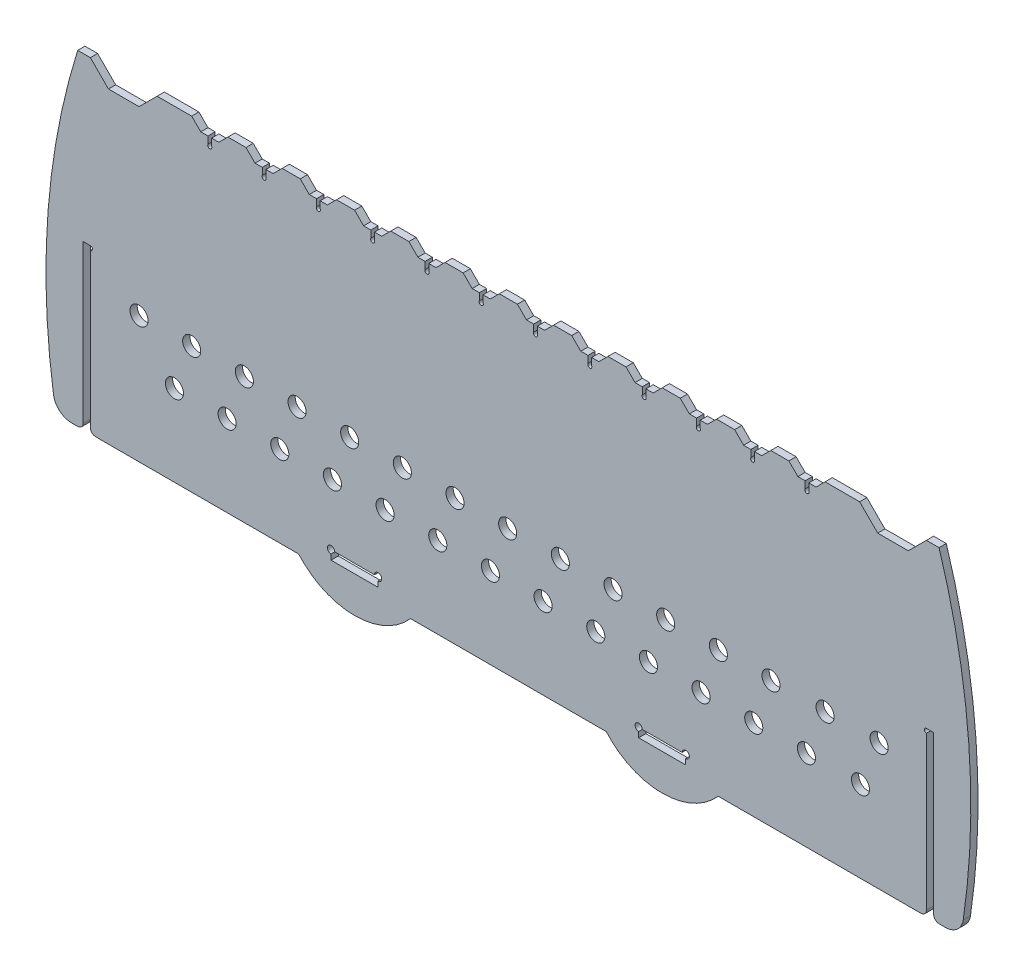
SolidWorks part; units mm, degrees
ref_plane "Спереди" through (0, 0, 0) normal (0, 0, 1) x (1, 0, 0)
ref_plane "Сверху" through (0, 0, 0) normal (0, 1, 0) x (1, 0, 0)
ref_plane "Справа" through (0, 0, 0) normal (1, 0, 0) x (0, 0, -1)
sketch "Эскиз1" plane through (0, 0, 0) normal (0, 0, 1) x (1, 0, 0)
  line L0 (152, 6) -> (178, 6)
  line L1 (8.5269, 0) -> (12, 0)
  line L2 (152, 6) -> (152, 9)
  line L3 (55.8972, 180) -> (45.8972, 170)
  line L4 (178, 6) -> (178, 9)
  line L5 (154, 11) -> (176, 11)
  line L6 (15, 3) -> (15, 90)
  line L7 (485, 3) -> (485, 90)
  line L8 (19, 87.6915) -> (19, 3)
  line L9 (481, 87.6915) -> (481, 3)
  line L10 (29, 170) -> (45.8972, 170)
  line L11 (84, 175) -> (84, 171.1094)
  line L12 (86, 175) -> (86, 171.1094)
  line L13 (84, 175) -> (80, 175)
  line L14 (322, 6) -> (348, 6)
  line L15 (22, 0) -> (134.0741, 0)
  line L16 (324, 11) -> (346, 11)
  line L17 (195.9259, 0) -> (304.0741, 0)
  line L18 (485, 90) -> (481, 90)
  line L19 (365.9259, 0) -> (478, 0)
  line L20 (444.1028, 180) -> (454.1028, 170)
  line L21 (488, 0) -> (491.4731, 0)
  line L22 (348, 6) -> (348, 9)
  line L23 (114, 175) -> (114, 171.1094)
  line L24 (116, 175) -> (116, 171.1094)
  line L25 (19, 180) -> (29, 170)
  line L26 (481, 180) -> (471, 170)
  line L27 (19, 180) -> (12, 180)
  line L28 (481, 180) -> (488, 180)
  line L29 (19, 90) -> (15, 90)
  line L30 (322, 6) -> (322, 9)
  line L31 (144, 175) -> (144, 171.1094)
  line L32 (146, 175) -> (146, 171.1094)
  line L33 (174, 175) -> (174, 171.1094)
  line L34 (176, 175) -> (176, 171.1094)
  line L35 (204, 175) -> (204, 171.1094)
  line L36 (206, 175) -> (206, 171.1094)
  line L37 (234, 175) -> (234, 171.1094)
  line L38 (236, 175) -> (236, 171.1094)
  line L39 (264, 175) -> (264, 171.1094)
  line L40 (266, 175) -> (266, 171.1094)
  line L41 (294, 175) -> (294, 171.1094)
  line L42 (296, 175) -> (296, 171.1094)
  line L43 (324, 175) -> (324, 171.1094)
  line L44 (326, 175) -> (326, 171.1094)
  line L45 (354, 175) -> (354, 171.1094)
  line L46 (356, 175) -> (356, 171.1094)
  line L47 (384, 175) -> (384, 171.1094)
  line L48 (386, 175) -> (386, 171.1094)
  line L49 (414, 175) -> (414, 171.1094)
  line L50 (416, 175) -> (416, 171.1094)
  line L51 (114, 175) -> (110, 175)
  line L52 (144, 175) -> (140, 175)
  line L53 (174, 175) -> (170, 175)
  line L54 (204, 175) -> (200, 175)
  line L55 (234, 175) -> (230, 175)
  line L56 (264, 175) -> (260, 175)
  line L57 (294, 175) -> (290, 175)
  line L58 (324, 175) -> (320, 175)
  line L59 (354, 175) -> (350, 175)
  line L60 (384, 175) -> (380, 175)
  line L61 (414, 175) -> (410, 175)
  line L119 (245, 180) -> (255, 180)
  line L120 (105, 180) -> (110, 175)
  line L122 (180, 175) -> (176, 175)
  line L127 (150, 175) -> (146, 175)
  line L128 (300, 175) -> (296, 175)
  line L129 (345, 180) -> (350, 175)
  line L130 (155, 180) -> (165, 180)
  line L131 (185, 180) -> (195, 180)
  line L133 (75, 180) -> (80, 175)
  line L134 (125, 180) -> (120, 175)
  line L137 (345, 180) -> (335, 180)
  line L140 (215, 180) -> (210, 175)
  line L142 (285, 180) -> (290, 175)
  line L146 (215, 180) -> (225, 180)
  line L147 (270, 175) -> (266, 175)
  line L150 (390, 175) -> (386, 175)
  line L151 (375, 180) -> (380, 175)
  line L153 (444.1028, 180) -> (425, 180)
  line L156 (155, 180) -> (150, 175)
  line L160 (405, 180) -> (395, 180)
  line L164 (365, 180) -> (360, 175)
  line L165 (285, 180) -> (275, 180)
  line L166 (90, 175) -> (86, 175)
  line L167 (255, 180) -> (260, 175)
  line L168 (120, 175) -> (116, 175)
  line L170 (471, 170) -> (454.1028, 170)
  line L171 (375, 180) -> (365, 180)
  line L172 (55.8972, 180) -> (75, 180)
  line L173 (165, 180) -> (170, 175)
  line L174 (210, 175) -> (206, 175)
  line L175 (305, 180) -> (300, 175)
  line L176 (330, 175) -> (326, 175)
  line L177 (360, 175) -> (356, 175)
  line L179 (125, 180) -> (135, 180)
  line L182 (405, 180) -> (410, 175)
  line L183 (420, 175) -> (416, 175)
  line L187 (245, 180) -> (240, 175)
  line L191 (315, 180) -> (320, 175)
  line L194 (135, 180) -> (140, 175)
  line L196 (425, 180) -> (420, 175)
  line L197 (185, 180) -> (180, 175)
  line L199 (240, 175) -> (236, 175)
  line L204 (275, 180) -> (270, 175)
  line L205 (95, 180) -> (90, 175)
  line L206 (395, 180) -> (390, 175)
  line L208 (195, 180) -> (200, 175)
  line L209 (225, 180) -> (230, 175)
  line L210 (335, 180) -> (330, 175)
  line L211 (95, 180) -> (105, 180)
  line L215 (315, 180) -> (305, 180)
  arc A0 (15, 3) -> (12, 0) centre (12, 3) cw
  arc A1 (19, 3) -> (22, 0) centre (22, 3) ccw
  arc A2 (481, 3) -> (478, 0) centre (478, 3) cw
  arc A3 (488, 0) -> (485, 3) centre (488, 3) cw
  circle A4 centre (45.8972, 70) radius 5
  circle A5 centre (65.4662, 45) radius 5
  circle A6 centre (75, 70) radius 5
  circle A7 centre (94.569, 45) radius 5
  circle A8 centre (104.1028, 70) radius 5
  circle A9 centre (123.6717, 45) radius 5
  circle A10 centre (133.2055, 70) radius 5
  circle A11 centre (152.7745, 45) radius 5
  circle A12 centre (162.3083, 70) radius 5
  circle A13 centre (181.8772, 45) radius 5
  circle A14 centre (191.411, 70) radius 5
  circle A15 centre (210.98, 45) radius 5
  circle A16 centre (220.5138, 70) radius 5
  circle A17 centre (240.0827, 45) radius 5
  circle A18 centre (249.6165, 70) radius 5
  circle A19 centre (269.1855, 45) radius 5
  circle A20 centre (278.7193, 70) radius 5
  circle A21 centre (298.2882, 45) radius 5
  circle A22 centre (307.822, 70) radius 5
  circle A23 centre (327.391, 45) radius 5
  circle A24 centre (336.9248, 70) radius 5
  circle A25 centre (356.4937, 45) radius 5
  circle A26 centre (366.0275, 70) radius 5
  circle A27 centre (385.5965, 45) radius 5
  circle A28 centre (395.1303, 70) radius 5
  circle A29 centre (414.6992, 45) radius 5
  circle A30 centre (425, 70) radius 5
  circle A31 centre (444.569, 45) radius 5
  circle A32 centre (454.8697, 70) radius 5
  arc A33 (134.0741, 0) -> (195.9259, 0) centre (165, 27.1575) ccw
  arc A34 (304.0741, 0) -> (365.9259, 0) centre (335, 27.1575) ccw
  arc A35 (12, 180) -> (-1.3647, 8.5313) centre (379.5877, 65.0942) ccw
  arc A36 (488, 180) -> (501.3647, 8.5313) centre (120.4123, 65.0942) cw
  arc A37 (-1.3647, 8.5313) -> (8.5269, 0) centre (8.5269, 10) ccw
  arc A38 (501.3647, 8.5313) -> (491.4731, 0) centre (491.4731, 10) cw
  arc A39 (19, 87.6915) -> (19, 90) centre (19, 88.8457) ccw
  arc A40 (178, 9) -> (176, 11) centre (178, 11) ccw
  arc A41 (481, 87.6915) -> (481, 90) centre (481, 88.8457) cw
  arc A42 (154, 11) -> (152, 9) centre (152, 11) ccw
  arc A43 (348, 9) -> (346, 11) centre (348, 11) ccw
  arc A44 (324, 11) -> (322, 9) centre (322, 11) ccw
  arc A45 (84, 171.1094) -> (86, 171.1094) centre (85, 170.5547) ccw
  arc A46 (114, 171.1094) -> (116, 171.1094) centre (115, 170.5547) ccw
  arc A47 (144, 171.1094) -> (146, 171.1094) centre (145, 170.5547) ccw
  arc A48 (174, 171.1094) -> (176, 171.1094) centre (175, 170.5547) ccw
  arc A49 (204, 171.1094) -> (206, 171.1094) centre (205, 170.5547) ccw
  arc A50 (234, 171.1094) -> (236, 171.1094) centre (235, 170.5547) ccw
  arc A51 (264, 171.1094) -> (266, 171.1094) centre (265, 170.5547) ccw
  arc A52 (294, 171.1094) -> (296, 171.1094) centre (295, 170.5547) ccw
  arc A53 (324, 171.1094) -> (326, 171.1094) centre (325, 170.5547) ccw
  arc A54 (354, 171.1094) -> (356, 171.1094) centre (355, 170.5547) ccw
  arc A55 (384, 171.1094) -> (386, 171.1094) centre (385, 170.5547) ccw
  arc A56 (414, 171.1094) -> (416, 171.1094) centre (415, 170.5547) ccw
  point P34 (485, 0)
  point P105 (0, 0)
  point P108 (500, 0)
  point P122 (84, 170)
  point P124 (86, 170)
  dimension "D1" = 12
extrude "Бобышка-Вытянуть1" add sketch "Эскиз1" along normal blind 4
